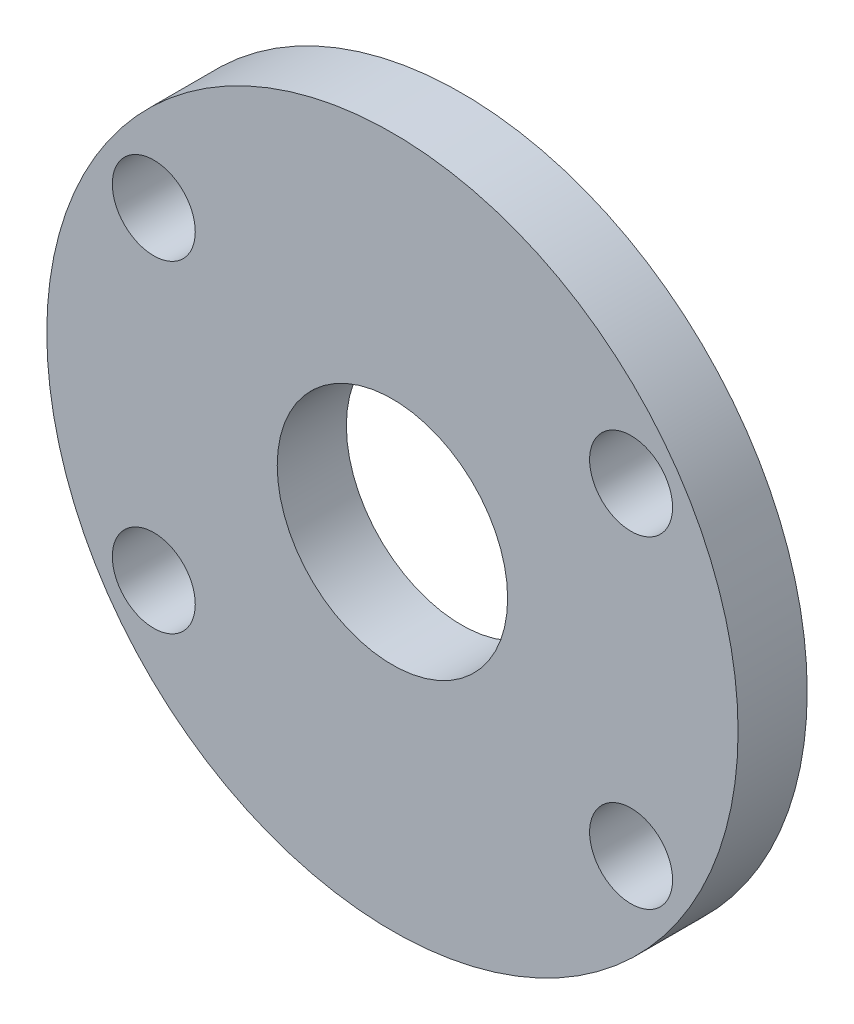
SolidWorks part; units mm, degrees
ref_plane "前视基准面" through (0, 0, 0) normal (0, 0, 1) x (1, 0, 0)
ref_plane "上视基准面" through (0, 0, 0) normal (0, 1, 0) x (1, 0, 0)
ref_plane "右视基准面" through (0, 0, 0) normal (1, 0, 0) x (0, 0, -1)
other "Configuration Table"
sketch "草图1" plane through (0, 0, 0) normal (0, 0, 1) x (1, 0, 0)
  circle A0 centre (0, 0) radius 15
  dimension "D1" = 30
extrude "凸台-拉伸1" add sketch "草图1" along normal blind 3
sketch "草图2" plane through (0, 0, 3) normal (0, 0, 1) x (1, 0, 0)
  circle A0 centre (0, 0) radius 5
  dimension "D1" = 10
extrude "切除-拉伸1" cut sketch "草图2" against normal up to next
sketch "草图3" plane through (0, 0, 3) normal (0, 0, 1) x (1, 0, 0)
  line L0 (-10.3562, -7) -> (10.3562, -7) construction
  line L1 (-0.4047, 0) -> (-50000.4047, 0) construction
  circle A0 centre (0, 0) radius 12.5 construction
  circle A1 centre (-10.3562, -7) radius 1.8
  circle A2 centre (10.3562, -7) radius 1.8
  circle A3 centre (10.3562, 7) radius 1.8
  circle A4 centre (-10.3562, 7) radius 1.8
  dimension "D1" = 25
  dimension "D3" = 3.6
  dimension "D4" = 3.6
  dimension "D2" = 7
extrude "切除-拉伸2" cut sketch "草图3" against normal up to next
